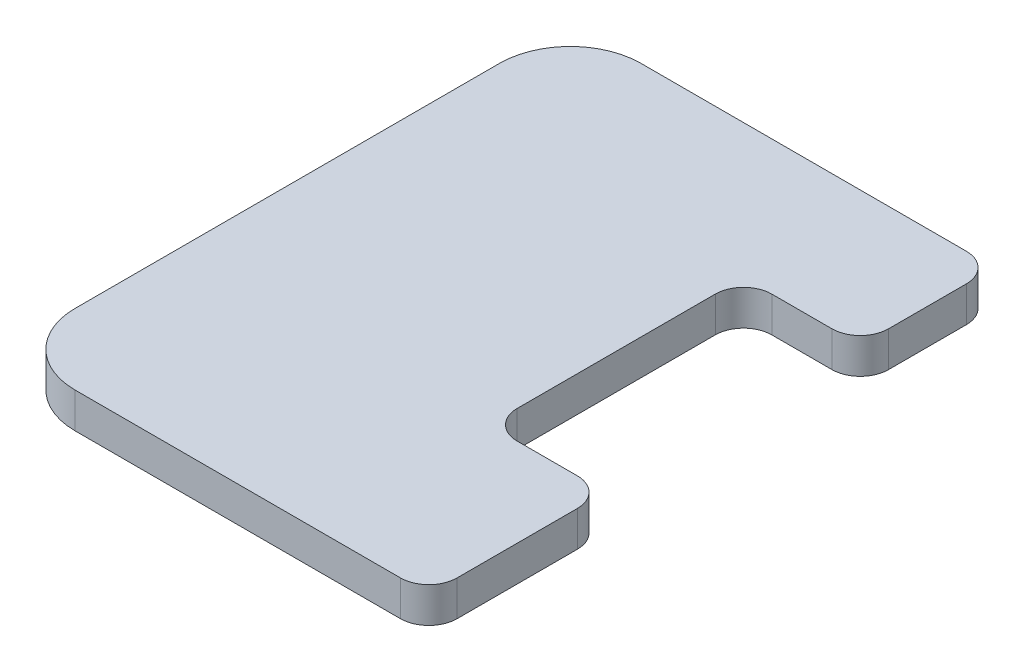
SolidWorks part; units mm, degrees
ref_plane "Front Plane" through (0, 0, 0) normal (0, 0, 1) x (1, 0, 0)
ref_plane "Top Plane" through (0, 0, 0) normal (0, 1, 0) x (1, 0, 0)
ref_plane "Right Plane" through (0, 0, 0) normal (1, 0, 0) x (0, 0, -1)
sketch "Sketch1" plane through (0, 0, 0) normal (0, 1, 0) x (1, 0, 0)
  line L1 (-19.05, -25.4) -> (19.05, -25.4)
  line L2 (-19.05, -25.4) -> (-19.05, 25.4)
  line L3 (-19.05, 25.4) -> (19.05, 25.4)
  line L4 (19.05, -25.4) -> (19.05, 25.4)
  line L5 (-19.05, -25.4) -> (19.05, 25.4) construction
  line L6 (-19.05, 25.4) -> (19.05, -25.4) construction
  point P0 (0, 0)
  dimension "D1" = 50.8
  dimension "D2" = 38.1
extrude "Boss-Extrude1" add sketch "Sketch1" along normal blind 3.175
sketch "Sketch2" plane through (0, 3.175, 0) normal (0, 1, 0) x (1, 0, 0)
  line L0 (19.05, -9.525) -> (8.5725, -9.525)
  line L1 (19.05, -25.4) -> (19.05, 25.4) construction
  line L2 (8.5725, -9.525) -> (8.5725, 13.335)
  line L3 (8.5725, 13.335) -> (19.05, 13.335)
  line L4 (19.05, 25.4) -> (-19.05, 25.4) construction
  line L5 (-19.05, -25.4) -> (19.05, -25.4) construction
  line L6 (19.05, -9.525) -> (19.05, 13.335)
  dimension "D1" = 12.065
  dimension "D2" = 15.875
  dimension "D3" = 10.4775
extrude "Cut-Extrude2" cut sketch "Sketch2" against normal through all
fillet "Fillet1" radius 2.54 6 edges at (19.05, 1.5875, 25.4) (19.05, 1.5875, -25.4) (19.05, 1.5875, 9.525) (8.5725, 1.5875, 9.525) (19.05, 1.5875, -13.335) (8.5725, 1.5875, -13.335)
fillet "Fillet2" radius 6.35 2 edges at (-19.05, 1.5875, 25.4) (-19.05, 1.5875, -25.4)
